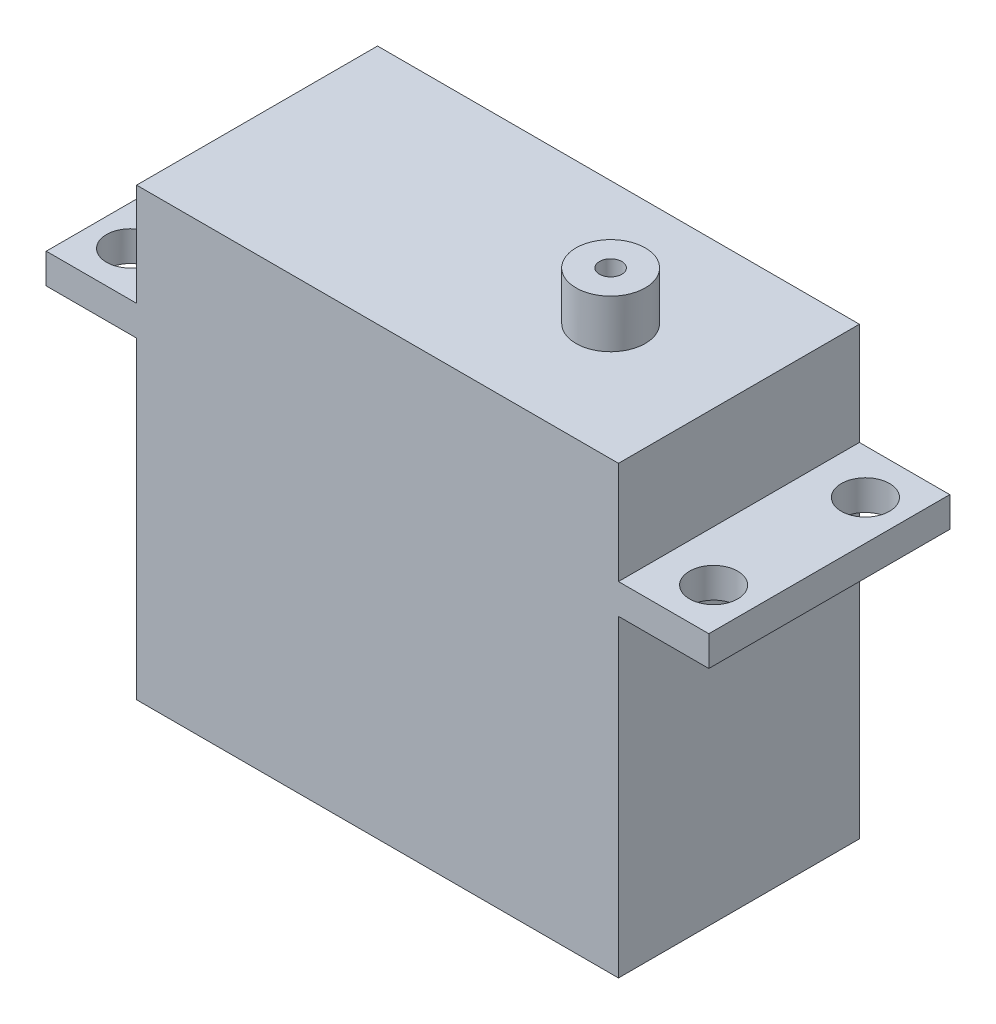
SolidWorks part; units mm, degrees
ref_plane "Front Plane" through (0, 0, 0) normal (0, 0, 1) x (1, 0, 0)
ref_plane "Top Plane" through (0, 0, 0) normal (0, 1, 0) x (1, 0, 0)
ref_plane "Right Plane" through (0, 0, 0) normal (1, 0, 0) x (0, 0, -1)
sketch "Sketch1" plane through (0, 0, 0) normal (0, 1, 0) x (1, 0, 0)
  line L1 (-20, -10) -> (20, -10)
  line L2 (-20, -10) -> (-20, 10)
  line L3 (-20, 10) -> (20, 10)
  line L4 (20, -10) -> (20, 10)
  line L5 (-20, -10) -> (20, 10) construction
  line L6 (-20, 10) -> (20, -10) construction
  point P0 (0, 0)
  dimension "D1" = 20
  dimension "D2" = 40
extrude "Boss-Extrude1" add sketch "Sketch1" along normal blind 37
ref_plane "Plane1" through (0, 26, 0) normal (0, 1, 0) x (1, 0, 0)
sketch "Sketch2" plane through (0, 26, 0) normal (0, 1, 0) x (1, 0, 0)
  line L0 (-20, -10) -> (20, -10) construction
  line L1 (20, 10) -> (27.5, 10)
  line L2 (20, 10) -> (20, -10)
  line L3 (20, -10) -> (27.5, -10)
  line L4 (27.5, 10) -> (27.5, -10)
  line L5 (0, -14.3) -> (0, 14.3) construction
  line L6 (-20, -10) -> (-27.5, -10)
  line L7 (-27.5, 10) -> (-27.5, -10)
  line L8 (-20, 10) -> (-27.5, 10)
  line L9 (-20, 10) -> (-20, -10)
  dimension "D1" = 7.5
extrude "Boss-Extrude2" add sketch "Sketch2" along normal blind 2.5
hole_wizard "Ø4.0 (4) Diameter Hole1" positions "Sketch3" profile "Sketch4" hole size "Ø4.0" standard "ANSI Metric" end condition through all
sketch "Sketch3" plane through (0, 28.5, 0) normal (0, 1, 0) x (1, 0, 0)
  line L1 (-24.2, 6.3) -> (24.2, 6.3) construction
  line L2 (-24.2, 6.3) -> (-24.2, -6.3) construction
  line L3 (-24.2, -6.3) -> (24.2, -6.3) construction
  line L4 (24.2, 6.3) -> (24.2, -6.3) construction
  line L5 (-27.5, 10) -> (-27.5, -10) construction
  line L6 (27.5, -10) -> (27.5, 10) construction
  line L7 (-27.5, 0) -> (27.5, 0) construction
  line L9 (-20, 10) -> (-27.5, 10) construction
  point P0 (-24.2, -6.3)
  point P2 (-24.2, 6.3)
  point P4 (24.2, 6.3)
  point P6 (24.2, -6.3)
  point P59 (-24.2, 0)
  dimension "D1" = 3.3
  dimension "D2" = 3.3
  dimension "D3" = 3.7
sketch "Sketch4" plane through (-24.2, 28.5, 6.3) normal (1, 0, 0) x (0, 0, 1)
  line L0 (0, 0) -> (0, 28.5)
  line L1 (0, 28.5) -> (2, 28.5)
  line L2 (2, 28.5) -> (2, 0)
  line L5 (2, 0) -> (0, 0)
  line L11 (0, -6.35) -> (0, 107.95) construction
  dimension "Thru Hole Dia." = 4
  dimension "Thru Hole Depth" = 28.5
sketch "Sketch5" plane through (0, 37, 0) normal (0, 1, 0) x (1, 0, 0)
  line L1 (-20, -10) -> (20, -10) construction
  line L2 (20, 10) -> (20, -10) construction
  circle A0 centre (9.625, -0.275) radius 2.875
  dimension "D1" = 5.75
  dimension "D2" = 9.725
  dimension "D3" = 10.375
extrude "Boss-Extrude3" add sketch "Sketch5" along normal blind 4
hole_wizard "Ø1.85 (1.85) Diameter Hole1" positions "Sketch6" profile "Sketch7" hole size "Ø1.85" standard "ANSI Metric"
sketch "Sketch6" plane through (0, 41, 0) normal (0, 1, 0) x (1, 0, 0)
  line L0 (9.625, 2.6) -> (9.625, -3.15) construction
  line L2 (6.75, -0.275) -> (12.5, -0.275) construction
  circle A0 centre (9.625, -0.275) radius 2.875 construction
  circle A1 centre (9.625, -0.275) radius 2.875 construction
  point P0 (9.625, -0.275)
  point P15 (0, 0)
  point P16 (9.625, -0.275)
sketch "Sketch7" plane through (9.625, 41, 0.275) normal (1, 0, 0) x (0, 0, 1)
  line L0 (0, 0) -> (0, 4.5558)
  line L1 (0, 4.5558) -> (0.925, 4)
  line L2 (0.925, 4) -> (0.925, 0)
  line L5 (0.925, 0) -> (0, 0)
  line L10 (0, 4.5558) -> (-0.925, 4) construction
  line L11 (0, -6.35) -> (0, 107.95) construction
  dimension "Hole Dia." = 1.85
  dimension "Hole Depth" = 4
  dimension "Drill Angle" = 118
equation "\"D1@Sketch2\"=(55-40)/2"
equation "\"D1@Sketch3\"=1.3 + 2"
equation "\"D2@Sketch3\"=\"D1@Sketch3\""
equation "\"D3@Sketch3\"= 1.7 + 2"
equation "\"D2@Sketch5\"=(\"D1@Sketch5\"/2) + 6.85"
equation "\"D3@Sketch5\"=(\"D1@Sketch5\"/2) + 7.5"
equation "\"D1@Boss-Extrude3\"=41-37mm"
